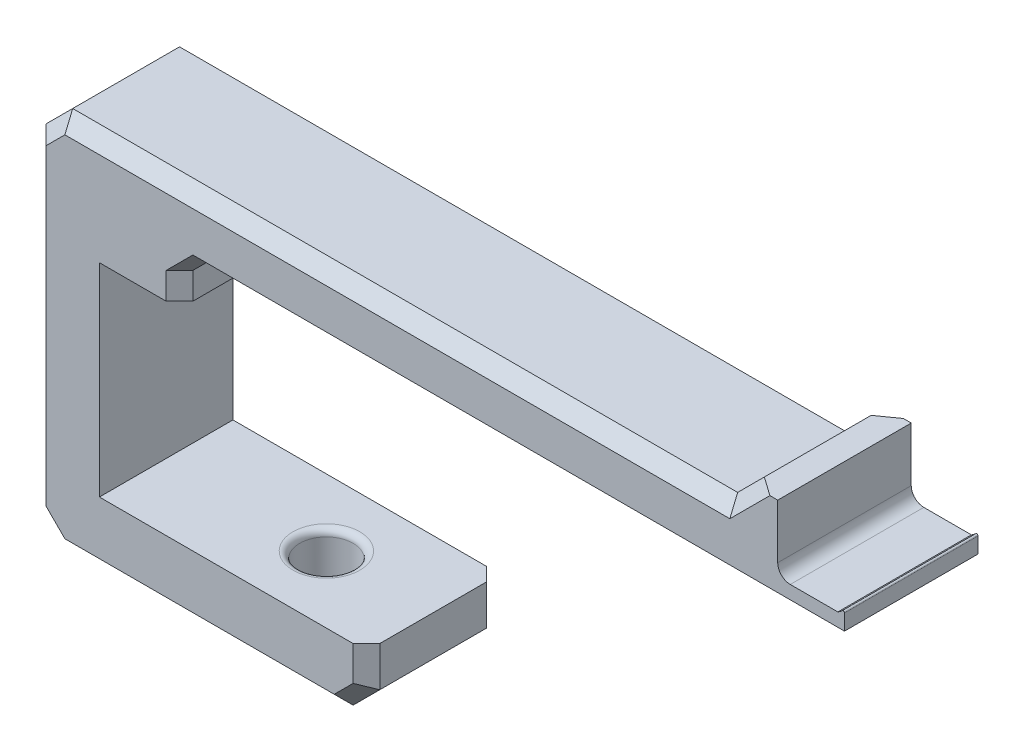
SolidWorks part; units mm, degrees
ref_plane "Plano frontal" through (0, 0, 0) normal (0, 0, 1) x (1, 0, 0)
ref_plane "Plano superior" through (0, 0, 0) normal (0, 1, 0) x (1, 0, 0)
ref_plane "Plano direito" through (0, 0, 0) normal (1, 0, 0) x (0, 0, -1)
sketch "Esboço1" plane through (0, 0, 0) normal (0, 0, 1) x (1, 0, 0)
  line L0 (57, 14.25) -> (7.2, 14.25)
  line L1 (7.2, 11.25) -> (1.2, 11.25)
  line L3 (1.2, -3.95) -> (21.2, -3.95)
  line L4 (21.2, -3.95) -> (21.2, -8.95)
  line L5 (21.2, -8.95) -> (-3.8, -8.95)
  line L6 (-3.8, -8.95) -> (-3.8, 19.25)
  line L7 (7.2, 14.25) -> (7.2, 11.25)
  line L9 (1.2, 11.25) -> (1.2, -3.95)
  line L10 (57, 14.25) -> (57, 16.25)
  line L11 (56.5044, 16.25) -> (52, 16.25)
  line L12 (52, 16.25) -> (52, 19.25)
  line L13 (52, 19.25) -> (-3.8, 19.25)
  line L14 (57, 16.25) -> (57, 16.4263)
  arc A0 (57, 16.4263) -> (56.8291, 16.4969) centre (56.9, 16.4263) ccw
  arc A1 (56.5044, 16.25) -> (56.8291, 16.4969) centre (55.7735, 17.5484) ccw
  dimension "D12" = 0.1
  dimension "D2" = 20
  dimension "D3" = 15.2
  dimension "D4" = 6
  dimension "D5" = 3
  dimension "D6" = 5
  dimension "D7" = 2
  dimension "D8" = 5
  dimension "D10" = 55.8
  dimension "D11" = 5
  dimension "D13" = 0.1763
  dimension "D14" = 0.4956
extrude "Ressalto-extrusão1" add sketch "Esboço1" along normal blind 10
sketch "Esboço3" plane through (0, -8.95, 0) normal (0, -1, 0) x (1, 0, 0)
  line L0 (21.2, 5) -> (13.2, 5) construction
  line L1 (21.2, 10) -> (21.2, 0) construction
  circle A0 centre (13.2, 5) radius 2
  dimension "D1" = 4
  dimension "D2" = 8
extrude "Corte-extrusão1" cut sketch "Esboço3" against normal blind 15
chamfer "Chanfro1" distance 1.6 angle 45 1 edges at (13.2, -8.95, 3)
fillet "Filete1" radius 0.5 1 edges at (13.2, -3.95, 3)
fillet "Filete2" radius 0.94 1 edges at (52, 16.25, 5)
sketch "Esboço5" plane through (0, 0, 10) normal (0, 0, 1) x (1, 0, 0)
  line L0 (52, 19.25) -> (52, 21.25)
  line L1 (52, 21.25) -> (50, 21.25)
  line L2 (50, 21.25) -> (48, 19.25)
  line L3 (52, 19.25) -> (-3.8, 19.25) construction
  line L4 (48, 19.25) -> (52, 19.25)
  dimension "D1" = 135
  dimension "D2" = 2
  dimension "D3" = 2
extrude "Ressalto-extrusão3" add sketch "Esboço5" against normal up to surface (10 mm away) up to face at (29.0474, 9.7443, 0)
chamfer "Chanfro5" distance 2 angle 45 3 edges at (21.2, -8.95, 5) (-3.8, -8.95, 5) (-3.8, 19.25, 5)
chamfer "Chanfro4" distance 1 angle 45 22 edges at (32.1, 14.25, 0) (32.1, 14.25, 10) (57, 14.25, 5) (49, 20.25, 10) (23.1, 19.25, 0) (23.1, 19.25, 10) (-2.8, 18.25, 10) (-2.8, 18.25, 0) (-3.8, 5.15, 0) (-3.8, 5.15, 10) (-2.8, -7.95, 10) (-2.8, -7.95, 0) (8.7, -8.95, 10) (8.7, -8.95, 0) (20.2, -7.95, 10) (20.2, -7.95, 0) (21.2, -5.45, 10) (21.2, -5.45, 0) (49, 20.25, 0) (7.2, 12.75, 0) (7.2, 12.75, 10) (7.2, 14.25, 5)
